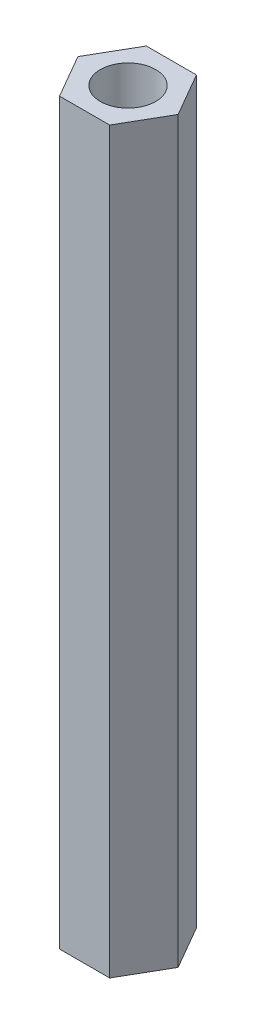
SolidWorks part; units mm, degrees
material "黄铜"
ref_plane "前视基准面" through (0, 0, 0) normal (0, 0, 1) x (1, 0, 0)
ref_plane "上视基准面" through (0, 0, 0) normal (0, 1, 0) x (1, 0, 0)
ref_plane "右视基准面" through (0, 0, 0) normal (1, 0, 0) x (0, 0, -1)
other "Configuration Table"
sketch "草图1" plane through (0, 0, 0) normal (0, 1, 0) x (1, 0, 0)
  line L0 (-2.7135, 0) -> (2.7135, 0) construction
  line L1 (1.3568, -2.35) -> (2.7135, 0)
  line L2 (2.7135, 0) -> (1.3568, 2.35)
  line L3 (1.3568, 2.35) -> (-1.3568, 2.35)
  line L4 (-1.3568, 2.35) -> (-2.7135, 0)
  line L5 (-2.7135, 0) -> (-1.3568, -2.35)
  line L6 (-1.3568, -2.35) -> (1.3568, -2.35)
  circle A0 centre (0, 0) radius 2.35 construction
  circle A1 centre (0, 0) radius 1.5
  point P13 (0, 0)
  dimension "D2" = 3
  dimension "D1" = 4.7
extrude "凸台-拉伸1" add sketch "草图1" along normal blind 40
